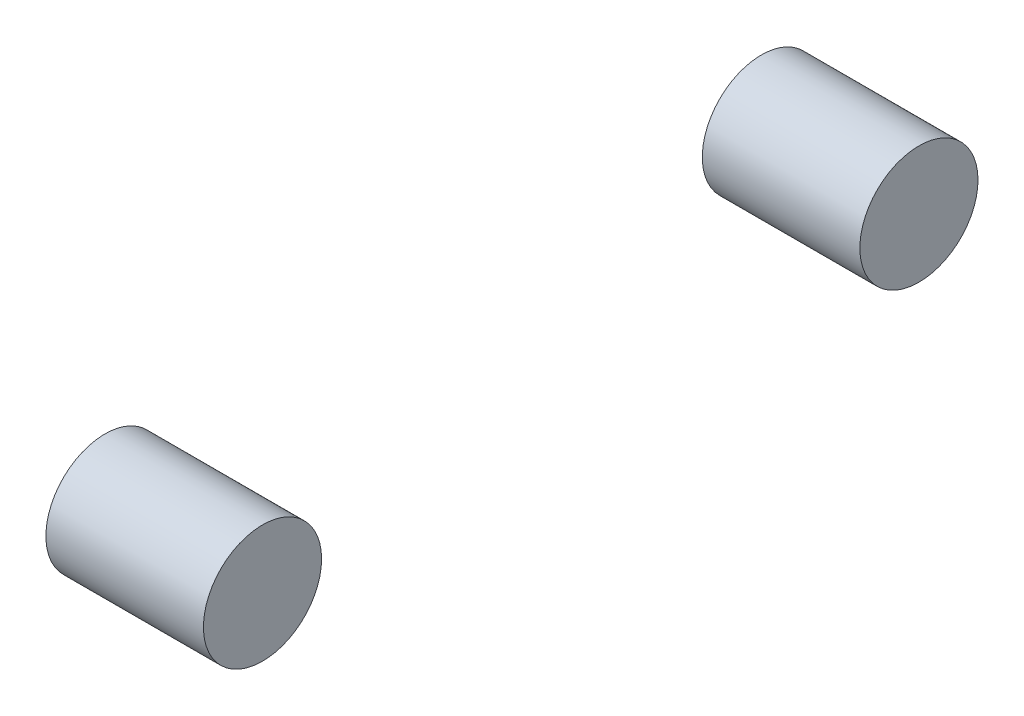
SolidWorks part; units mm, degrees
ref_plane "Front Plane" through (0, 0, 0) normal (0, 0, 1) x (1, 0, 0)
ref_plane "Top Plane" through (0, 0, 0) normal (0, 1, 0) x (1, 0, 0)
ref_plane "Right Plane" through (0, 0, 0) normal (1, 0, 0) x (0, 0, -1)
sketch "Sketch1" plane through (0, 0, 0) normal (1, 0, 0) x (0, 0, -1)
  circle A0 centre (500, -1650) radius 90
extrude "Boss-Extrude1" add sketch "Sketch1" along normal blind 240 from offset 1117.7127
sketch "Sketch2" plane through (0, 0, 0) normal (1, 0, 0) x (0, 0, -1)
  circle A0 centre (-500, -1650) radius 90
extrude "Boss-Extrude2" add sketch "Sketch2" along normal blind 240 from offset 1117.7127
